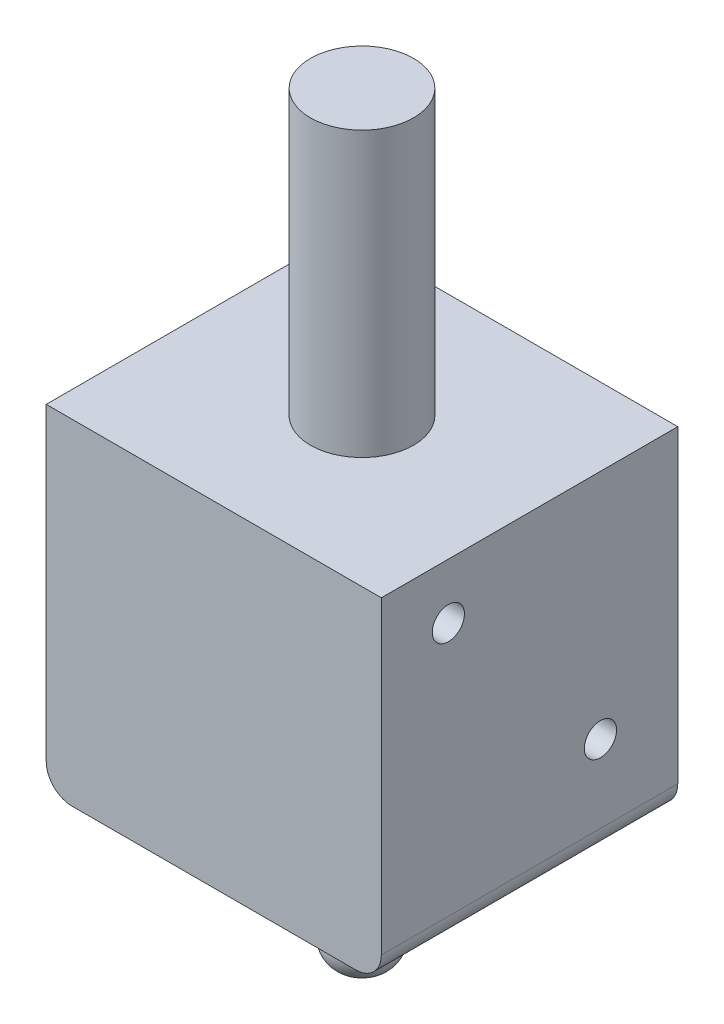
SolidWorks part; units mm, degrees
ref_plane "Front Plane" through (0, 0, 0) normal (0, 0, 1) x (1, 0, 0)
ref_plane "Top Plane" through (0, 0, 0) normal (0, 1, 0) x (1, 0, 0)
ref_plane "Right Plane" through (0, 0, 0) normal (1, 0, 0) x (0, 0, -1)
sketch "Sketch1" plane through (0, 0, 0) normal (0, 1, 0) x (1, 0, 0)
  line L1 (-13, -11.5) -> (13, -11.5)
  line L2 (-13, -11.5) -> (-13, 11.5)
  line L3 (-13, 11.5) -> (13, 11.5)
  line L4 (13, -11.5) -> (13, 11.5)
  line L5 (-13, -11.5) -> (13, 11.5) construction
  line L6 (-13, 11.5) -> (13, -11.5) construction
  point P0 (0, 0)
  dimension "D1" = 23
  dimension "D2" = 26
extrude "Boss-Extrude1" add sketch "Sketch1" along normal blind 26
sketch "Sketch2" plane through (13, 0, 0) normal (1, 0, 0) x (0, 0, -1)
  line L0 (5.5, 26) -> (5.5, 0) construction
  line L1 (-11.5, 26) -> (11.5, 26) construction
  line L2 (-6.3, 26) -> (-6.3, 0) construction
  line L3 (-11.5, 0) -> (11.5, 0) construction
  line L4 (-11.5, 26) -> (-11.5, 0) construction
  line L5 (-11.5, 21.7) -> (11.5, 21.7) construction
  line L6 (11.5, 26) -> (11.5, 0) construction
  line L7 (11.5, 8) -> (-11.5, 8) construction
  dimension "D1" = 5.2
  dimension "4.5" = 4.3
  dimension "D3" = 6
  dimension "D4" = 8
  dimension "D5" = 5.5
  dimension "D6" = 21.7
  dimension "D7" = 8
  dimension "D8" = 11.8
hole_wizard "M3 Tapped Hole1" positions "Sketch3" profile "Sketch4" tap size "M3" standard "ISO"
sketch "Sketch3" plane through (13, 0, 0) normal (1, 0, 0) x (0, 0, -1)
  line L1 (5.5, 26) -> (5.5, 0) construction
  line L2 (11.5, 8) -> (-11.5, 8) construction
  line L3 (-6.3, 26) -> (-6.3, 0) construction
  line L4 (-11.5, 21.7) -> (11.5, 21.7) construction
  point P0 (-6.3, 21.7)
  point P2 (5.5, 8)
sketch "Sketch4" plane through (13, 21.7, 6.3) normal (0, 1, 0) x (0, 0, -1)
  line L0 (0, 0) -> (0, 10.8511)
  line L1 (0, 10.8511) -> (1.25, 10.1)
  line L2 (1.25, 10.1) -> (1.25, 0)
  line L5 (1.25, 0) -> (0, 0)
  line L10 (0, 10.8511) -> (-1.25, 10.1) construction
  line L11 (0, -6.35) -> (0, 107.95) construction
  dimension "Tap Drill Dia." = 2.5
  dimension "Tap Drill Depth" = 10.1
  dimension "Drill Angle" = 118
cosmetic thread "Hole Thread1" parameters "D1"=8, "D2"=3
cosmetic thread "Hole Thread2" parameters "D1"=8, "D2"=3
fillet "Fillet1" radius 2 2 edges at (-13, 0, 0) (13, 0, 0)
sketch "Sketch5" plane through (0, 26, 0) normal (0, 1, 0) x (1, 0, 0)
  circle A0 centre (0, 0) radius 4
  dimension "D1" = 8
extrude "Boss-Extrude2" add sketch "Sketch5" along normal blind 22
sketch "Sketch6" plane through (0, 0, 0) normal (0, -1, 0) x (1, 0, 0)
  circle A0 centre (0, 0) radius 2.5
  dimension "D1" = 5
extrude "Boss-Extrude3" add sketch "Sketch6" along normal blind 11
fillet "Fillet2" radius 2 1 edges at (0, -11, -2.5)
